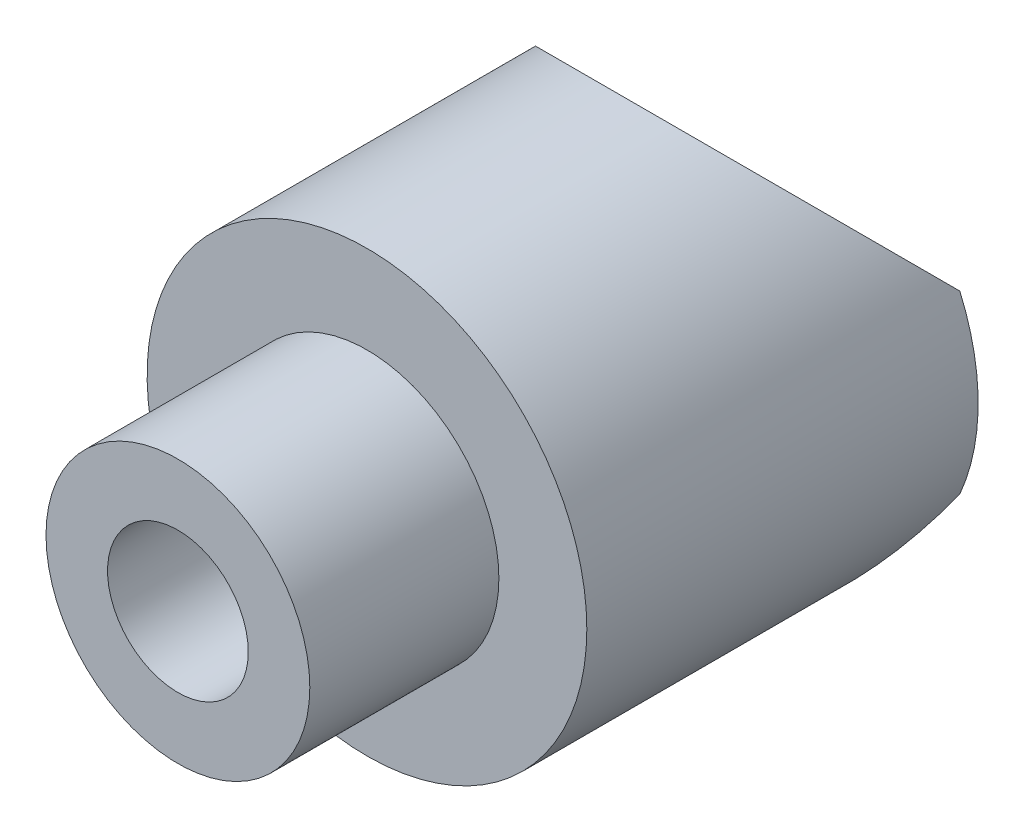
SolidWorks part; units mm, degrees
ref_plane "前视基准面" through (0, 0, 0) normal (0, 0, 1) x (1, 0, 0)
ref_plane "上视基准面" through (0, 0, 0) normal (0, 1, 0) x (1, 0, 0)
ref_plane "右视基准面" through (0, 0, 0) normal (1, 0, 0) x (0, 0, -1)
sketch "草图1" plane through (0, 0, 0) normal (0, 0, 1) x (1, 0, 0)
  circle A0 centre (0, 0) radius 5
  dimension "D1" = 10
extrude "凸台-拉伸1" add sketch "草图1" along normal blind 15
ref_plane "基准面1" through (0, 0, 13) normal (0, 0, 1) x (1, 0, 0)
sketch "草图2" plane through (0, 0, 13) normal (0, 0, 1) x (1, 0, 0)
  circle A0 centre (0, 0) radius 5 construction
  circle A1 centre (0, 0) radius 5
  circle A2 centre (0, 0) radius 3
  dimension "D1" = 6
extrude "切除-拉伸1" cut sketch "草图2" against normal blind 4
sketch "草图3" plane through (0, 0, 0) normal (0, 1, 0) x (1, 0, 0)
  circle A0 centre (0, 2) radius 5
  dimension "D1" = 10
  dimension "D2" = 2
extrude "切除-拉伸2" cut sketch "草图3" against normal mid plane 50
sketch "草图4" plane through (0, 0, 15) normal (0, 0, 1) x (1, 0, 0)
  circle A0 centre (0, 0) radius 1.6
  dimension "D1" = 3.2
extrude "切除-拉伸3" cut sketch "草图4" against normal through all
ref_plane "基准面2" through (0, 0, 11) normal (0, 0, 1) x (1, 0, 0)
sketch "草图5" plane through (0, 0, 11) normal (0, 0, 1) x (1, 0, 0)
  circle A0 centre (0, 0) radius 5 construction
  circle A1 centre (0, 0) radius 5
  circle A2 centre (0, 0) radius 3 construction
  circle A3 centre (0, 0) radius 3
extrude "切除-拉伸4" cut sketch "草图5" against normal mid plane 4.2
sketch "草图6" plane through (0, 0, 15) normal (0, 0, 1) x (1, 0, 0)
  circle A0 centre (0, 0) radius 3 construction
  circle A1 centre (0, 0) radius 3
extrude "切除-拉伸5" cut sketch "草图6" against normal blind 3 flip side to cut
sketch "草图7" plane through (0, 0, 15) normal (0, 0, 1) x (1, 0, 0)
  circle A1 centre (0, 0) radius 3
  circle A2 centre (0, 0) radius 3
  dimension "D1" = 0
extrude "切除-拉伸6" cut sketch "草图7" against normal blind 1.8
